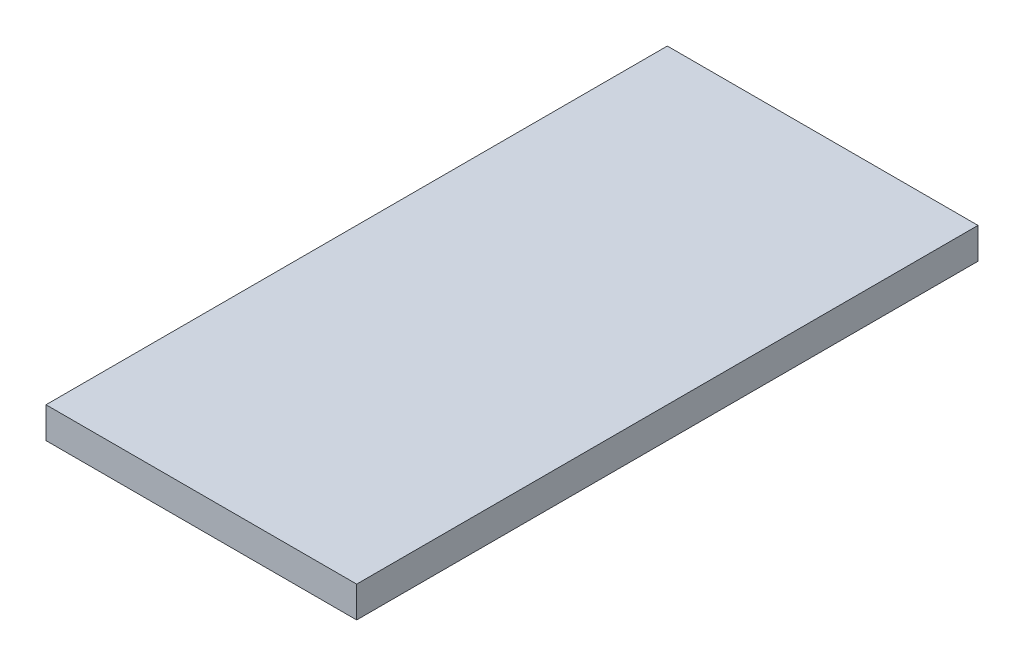
SolidWorks part; units mm, degrees
ref_plane "Płaszczyzna przednia" through (0, 0, 0) normal (0, 0, 1) x (1, 0, 0)
ref_plane "Płaszczyzna górna" through (0, 0, 0) normal (0, 1, 0) x (1, 0, 0)
ref_plane "Płaszczyzna prawa" through (0, 0, 0) normal (1, 0, 0) x (0, 0, -1)
sketch "Szkic1" plane through (0, 0, 0) normal (0, 1, 0) x (1, 0, 0)
  line L1 (0, 0) -> (50, 0)
  line L2 (0, 0) -> (0, 100)
  line L3 (0, 100) -> (50, 100)
  line L4 (50, 0) -> (50, 100)
  dimension "D1" = 100
  dimension "D2" = 50
extrude "Dodanie-wyciągnięcie1" add sketch "Szkic1" along normal blind 5
